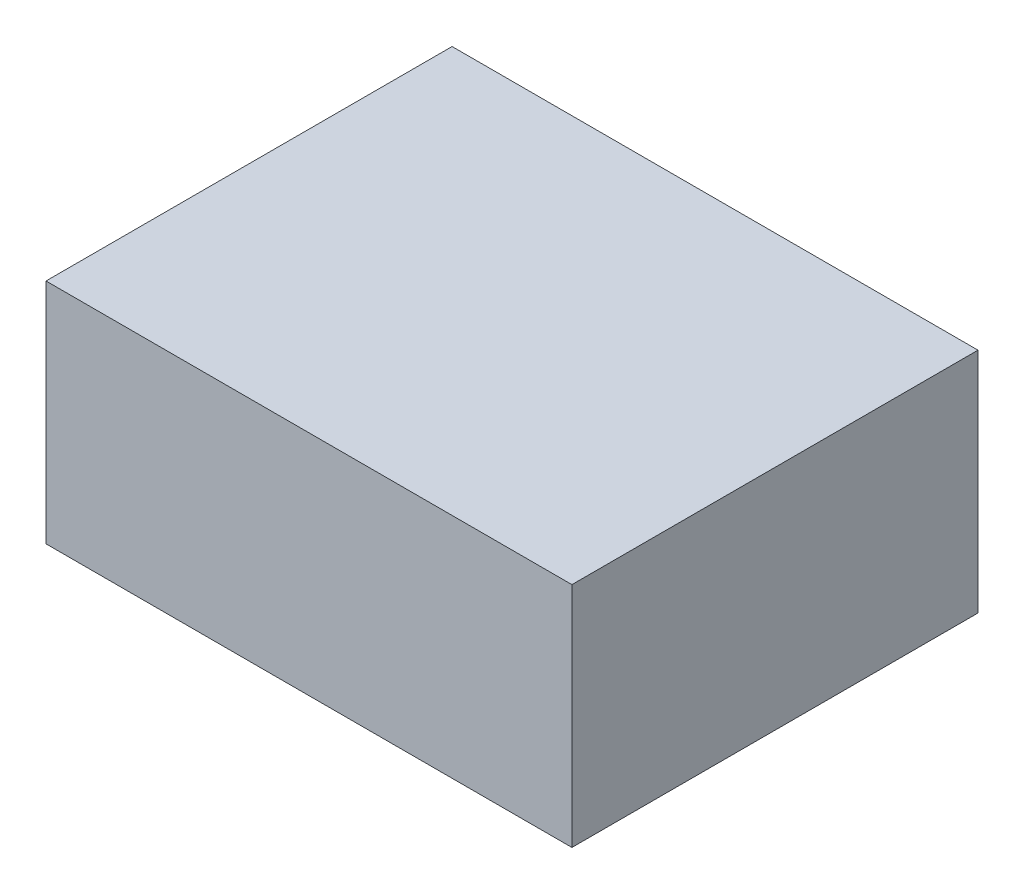
SolidWorks part; units mm, degrees
ref_plane "Front" through (0, 0, 0) normal (0, 0, 1) x (1, 0, 0)
ref_plane "Top" through (0, 0, 0) normal (0, 1, 0) x (1, 0, 0)
ref_plane "Right" through (0, 0, 0) normal (1, 0, 0) x (0, 0, -1)
sketch "Sketch1" plane through (0, 0, 0) normal (0, 1, 0) x (1, 0, 0)
  line L1 (-57.7541, -44.5949) -> (57.7541, -44.5949)
  line L2 (-57.7541, -44.5949) -> (-57.7541, 44.5949)
  line L3 (-57.7541, 44.5949) -> (57.7541, 44.5949)
  line L4 (57.7541, -44.5949) -> (57.7541, 44.5949)
  line L5 (-57.7541, -44.5949) -> (57.7541, 44.5949) construction
  line L6 (-57.7541, 44.5949) -> (57.7541, -44.5949) construction
  point P0 (0, 0)
extrude "Boss-Extrude1" add sketch "Sketch1" along normal blind 50
